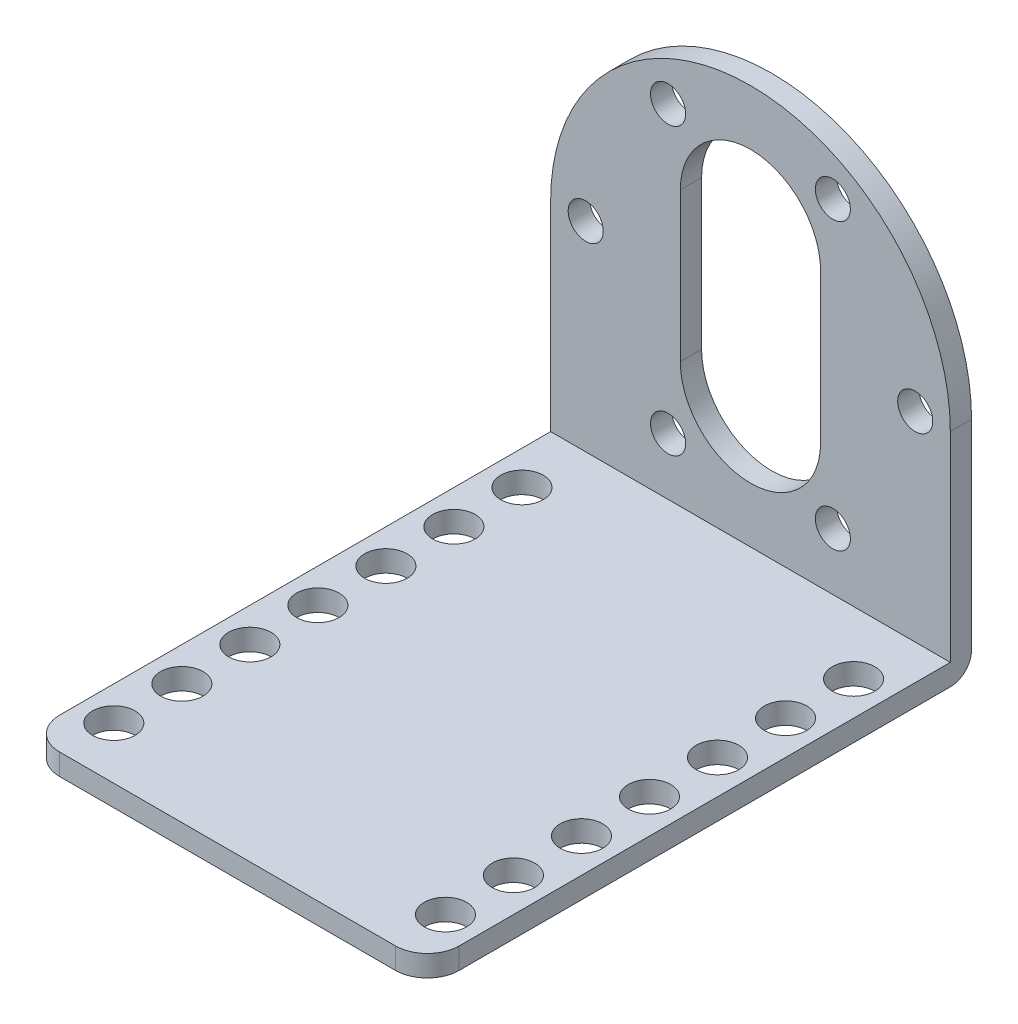
SolidWorks part; units mm, degrees
ref_plane "Front Plane" through (0, 0, 0) normal (0, 0, 1) x (1, 0, 0)
ref_plane "Top Plane" through (0, 0, 0) normal (0, 1, 0) x (1, 0, 0)
ref_plane "Right Plane" through (0, 0, 0) normal (1, 0, 0) x (0, 0, -1)
sketch "Sketch1" plane through (0, 0, 0) normal (0, 0, 1) x (1, 0, 0)
  line L0 (-18.8, 0) -> (-18.8, -20.8)
  line L1 (-18.8, -20.8) -> (18.8, -20.8)
  line L2 (18.8, -20.8) -> (18.8, 0)
  arc A0 (-18.8, 0) -> (18.8, 0) centre (0, 0) cw
  dimension "D1" = 37.6
  dimension "D2" = 18.8
  dimension "D3" = 20.8
  dimension "D4" = 18.8
  dimension "D5" = 18.8
extrude "Boss-Extrude1" add sketch "Sketch1" along normal blind 2
sketch "Sketch2" plane through (0, 0, 2) normal (0, 0, 1) x (1, 0, 0)
  line L0 (18.8, -20.8) -> (18.8, 0) construction
  line L1 (-18.8, -20.8) -> (18.8, -20.8)
  line L2 (-18.8, -20.8) -> (-18.8, -18.8)
  line L3 (-18.8, -18.8) -> (18.8, -18.8)
  line L4 (18.8, -20.8) -> (18.8, -18.8)
  dimension "D1" = 2
extrude "Boss-Extrude2" add sketch "Sketch2" along normal blind 49.2
fillet "Fillet1" radius 2 1 edges at (0, -20.8, 0)
fillet "Fillet2" radius 3 2 edges at (-18.8, -19.8, 51.2) (18.8, -19.8, 51.2)
sketch "Sketch3" plane through (0, -20.8, 0) normal (0, -1, 0) x (1, 0, 0)
  line L0 (-15.8, 51.2) -> (15.8, 51.2) construction
  line L1 (-18.8, 48.2) -> (-18.8, 2) construction
  circle A0 centre (-15.6, 46.3) radius 2
  circle A1 centre (15.6, 46.3) radius 2
  circle A2 centre (-15.6, 39.9) radius 2
  circle A3 centre (15.6, 39.9) radius 2
  circle A4 centre (-15.6, 33.5) radius 2
  circle A5 centre (15.6, 33.5) radius 2
  circle A6 centre (-15.6, 27.1) radius 2
  circle A7 centre (15.6, 27.1) radius 2
  circle A8 centre (-15.6, 20.7) radius 2
  circle A9 centre (15.6, 20.7) radius 2
  circle A10 centre (-15.6, 14.3) radius 2
  circle A11 centre (15.6, 14.3) radius 2
  circle A12 centre (-15.6, 7.9) radius 2
  circle A13 centre (15.6, 7.9) radius 2
  dimension "D1" = 4
  dimension "D2" = 4
  dimension "D3" = 4.9
  dimension "D4" = 4.9
  dimension "D5" = 31.2
  dimension "D6" = 3.2
  dimension "D7" = 7
extrude "Cut-Extrude1" cut sketch "Sketch3" against normal up to next
sketch "Sketch4" plane through (0, 0, 0) normal (0, 0, -1) x (-1, 0, 0)
  line L0 (-6.6, 7) -> (-6.6, -7)
  line L1 (6.6, 7) -> (6.6, -7)
  line L2 (18.8, -20.8) -> (-18.8, -20.8) construction
  arc A0 (-6.6, 7) -> (6.6, 7) centre (0, 7) cw
  arc A1 (-6.6, -7) -> (6.6, -7) centre (0, -7) ccw
  circle A2 centre (15.5, 0) radius 1.65
  circle A3 centre (7.75, -13.4234) radius 1.65
  circle A4 centre (-7.75, -13.4234) radius 1.65
  circle A5 centre (-15.5, 0) radius 1.65
  circle A6 centre (-7.75, 13.4234) radius 1.65
  circle A7 centre (7.75, 13.4234) radius 1.65
  point P23 (0, 0)
  dimension "D1" = 14
  dimension "D4" = 20.8
  dimension "D6" = 3.3
  dimension "D7" = 15.5
  dimension "D9" = 6.6
  dimension "D2" = 13.2
  dimension "D3" = 0
  dimension "D5" = 7
  dimension "D8" = 6
extrude "Cut-Extrude2" cut sketch "Sketch4" against normal up to next
